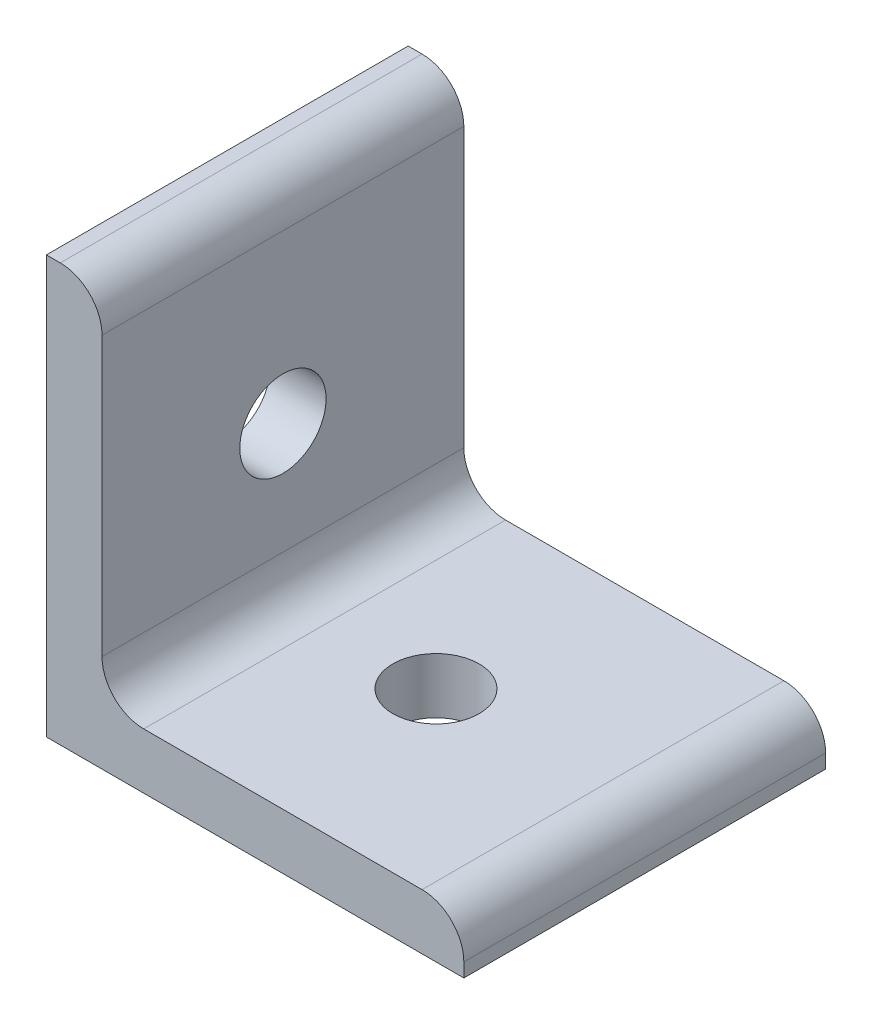
SolidWorks part; units mm, degrees
ref_plane "前视基准面" through (0, 0, 0) normal (0, 0, 1) x (1, 0, 0)
ref_plane "上视基准面" through (0, 0, 0) normal (0, 1, 0) x (1, 0, 0)
ref_plane "右视基准面" through (0, 0, 0) normal (1, 0, 0) x (0, 0, -1)
sketch "草图1" plane through (0, 0, 0) normal (0, 0, 1) x (1, 0, 0)
  line L0 (0, 0) -> (30, 0)
  line L1 (30, 0) -> (30, 4)
  line L2 (30, 4) -> (4, 4)
  line L3 (4, 4) -> (4, 30)
  line L4 (4, 30) -> (0, 30)
  line L5 (0, 30) -> (0, 0)
  dimension "D1" = 30
  dimension "D2" = 4
extrude "凸台-拉伸1" add sketch "草图1" along normal mid plane 26
hole_wizard "Ø6.2 (6.2) 直径孔1" positions "草图2" profile "草图3" hole size "Ø6.2" standard "ANSI Metric" end condition through all
sketch "草图2" plane through (0, 4, 0) normal (0, 1, 0) x (1, 0, 0)
  line L0 (0, 0) -> (15, 0)
  point P0 (15, 0)
  dimension "D1" = 15
sketch "草图3" plane through (15, 4, 0) normal (1, 0, 0) x (0, 0, 1)
  line L0 (0, 0) -> (0, 4)
  line L1 (0, 4) -> (3.1, 4)
  line L2 (3.1, 4) -> (3.1, 0)
  line L5 (3.1, 0) -> (0, 0)
  line L11 (0, -6.35) -> (0, 107.95) construction
  dimension "通孔孔直径" = 6.2
  dimension "通孔孔深度" = 4
hole_wizard "Ø6.2 (6.2) 直径孔2" positions "草图4" profile "草图5" hole size "Ø6.2" standard "ANSI Metric" end condition through all
sketch "草图4" plane through (4, 0, 0) normal (1, 0, 0) x (0, 0, -1)
  line L0 (0, 15) -> (0, 0)
  point P0 (0, 15)
  dimension "D1" = 15
sketch "草图5" plane through (4, 15, 0) normal (0, 1, 0) x (0, 0, -1)
  line L0 (0, 0) -> (0, 4)
  line L1 (0, 4) -> (3.1, 4)
  line L2 (3.1, 4) -> (3.1, 0)
  line L5 (3.1, 0) -> (0, 0)
  line L11 (0, -6.35) -> (0, 107.95) construction
  dimension "通孔孔直径" = 6.2
  dimension "通孔孔深度" = 4
fillet "圆角1" radius 3 3 edges at (4, 4, 0) (30, 4, 0) (4, 30, 0)
